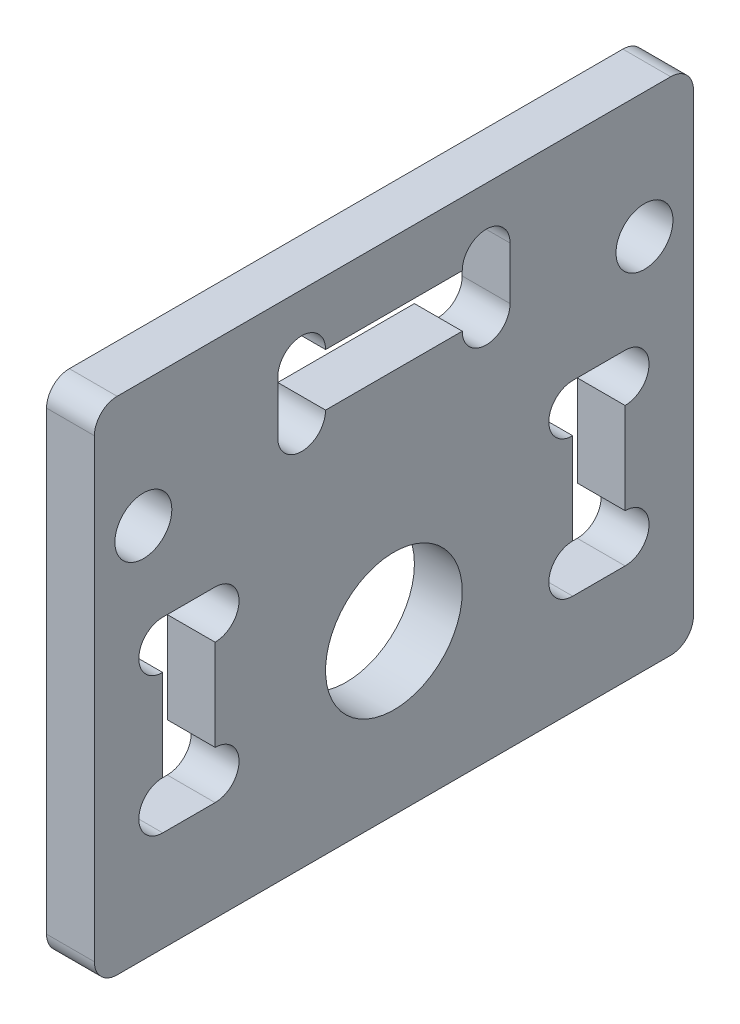
SolidWorks part; units mm, degrees
material "Thornel Mat VMA"
ref_plane "前视基准面" through (0, 0, 0) normal (0, 0, 1) x (1, 0, 0)
ref_plane "上视基准面" through (0, 0, 0) normal (0, 1, 0) x (1, 0, 0)
ref_plane "右视基准面" through (0, 0, 0) normal (1, 0, 0) x (0, 0, -1)
sketch "草图1" plane through (0, 0, 0) normal (1, 0, 0) x (0, 0, -1)
  line L0 (0, 0) -> (0, 5.143) construction
  line L1 (13.15, -11) -> (-13.15, -11)
  line L2 (13.15, -11) -> (13.15, 11)
  line L3 (13.15, 11) -> (-13.15, 11)
  line L4 (-13.15, -11) -> (-13.15, 11)
  line L5 (13.15, -11) -> (-13.15, 11) construction
  line L6 (13.15, 11) -> (-13.15, -11) construction
  line L7 (-7.85, -6.6) -> (-10.15, -6.6)
  line L8 (-7.85, -6.6) -> (-7.85, 1.6)
  line L9 (-7.85, 1.6) -> (-10.15, 1.6)
  line L10 (-10.15, -6.6) -> (-10.15, 1.6)
  line L11 (-7.85, -6.6) -> (-10.15, 1.6) construction
  line L12 (-7.85, 1.6) -> (-10.15, -6.6) construction
  line L13 (7.85, 1.6) -> (10.15, -6.6) construction
  line L14 (7.85, -6.6) -> (10.15, 1.6) construction
  line L15 (10.15, -6.6) -> (10.15, 1.6)
  line L16 (7.85, 1.6) -> (10.15, 1.6)
  line L17 (7.85, -6.6) -> (7.85, 1.6)
  line L18 (7.85, -6.6) -> (10.15, -6.6)
  line L19 (-13.15, 5.5) -> (-5.4278, 5.5) construction
  line L21 (5.1, 5.9) -> (-5.1, 5.9)
  line L22 (5.1, 5.9) -> (5.1, 8.2)
  line L23 (5.1, 8.2) -> (-5.1, 8.2)
  line L24 (-5.1, 5.9) -> (-5.1, 8.2)
  line L25 (5.1, 5.9) -> (-5.1, 8.2) construction
  line L26 (5.1, 8.2) -> (-5.1, 5.9) construction
  circle A0 centre (-7.85, 0.55) radius 1.05
  circle A1 centre (-10.15, 0.55) radius 1.05
  circle A2 centre (-10.15, -5.55) radius 1.05
  circle A3 centre (-7.85, -5.55) radius 1.05
  circle A4 centre (7.85, -5.55) radius 1.05
  circle A5 centre (10.15, -5.55) radius 1.05
  circle A6 centre (10.15, 0.55) radius 1.05
  circle A7 centre (7.85, 0.55) radius 1.05
  circle A8 centre (-11, 5.5) radius 1.25
  circle A9 centre (11, 5.5) radius 1.25
  circle A10 centre (-4.05, 8.2) radius 1.05
  circle A11 centre (4.05, 8.2) radius 1.05
  circle A12 centre (4.05, 5.9) radius 1.05
  circle A13 centre (-4.05, 5.9) radius 1.05
  circle A14 centre (0, -4) radius 3
  point P0 (0, 0)
  point P6 (-9, -2.5)
  point P33 (9, -2.5)
  point P40 (0, 7.05)
  dimension "D5" = 2.1
  dimension "D10" = 2.5
  dimension "D15" = 6
  dimension "D1" = 2.3
  dimension "D2" = 8.2
  dimension "D3" = 13.5
  dimension "D4" = 8.5
  dimension "D6" = 18
  dimension "D7" = 3
  dimension "D8" = 8
  dimension "D9" = 22
  dimension "D11" = 2.3
  dimension "D12" = 10.2
  dimension "D13" = 9.55
  dimension "D14" = 7
extrude "凸台-拉伸1" add sketch "草图1" along normal blind 2.1 contours L4 L1 L2 L3 A14 A13 L24 A10 L23 A11 L22 A12 L21 L17 A7 L16 A6 L15 A5 L18 A4 A3 L7 A2 L10 A1 L9 A0 L8 A8 A9
fillet "圆角1" radius 1 4 edges at (1.05, 11, -13.15) (1.05, -11, -13.15) (1.05, -11, 13.15) (1.05, 11, 13.15)
